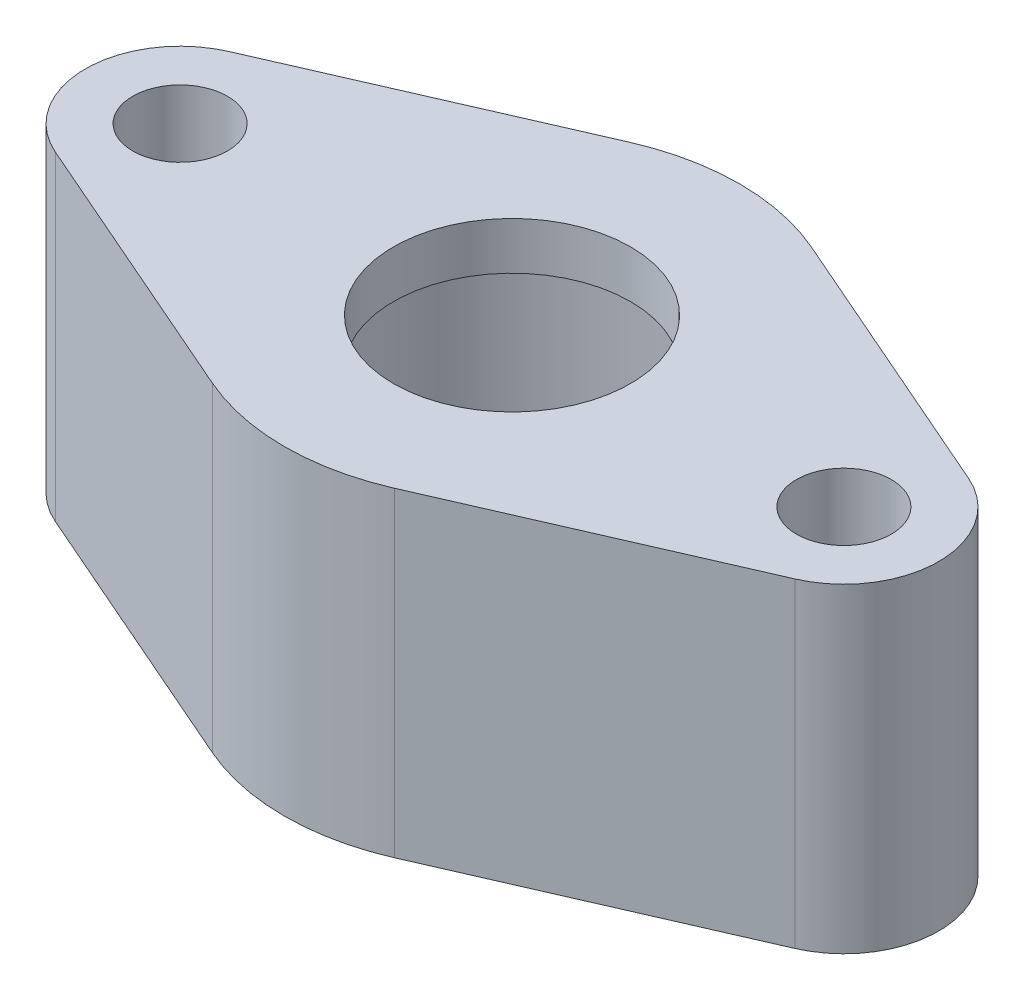
SolidWorks part; units mm, degrees
ref_plane "Front Plane" through (0, 0, 0) normal (0, 0, 1) x (1, 0, 0)
ref_plane "Top Plane" through (0, 0, 0) normal (0, 1, 0) x (1, 0, 0)
ref_plane "Right Plane" through (0, 0, 0) normal (1, 0, 0) x (0, 0, -1)
sketch "Sketch1" plane through (0, 0, 0) normal (0, 1, 0) x (1, 0, 0)
  line L0 (-3.84, 8.7985) -> (-15.6, 3.6661)
  line L1 (-15.6, -3.6661) -> (-3.84, -8.7985)
  line L2 (0, 0) -> (0, -7.6) construction
  line L3 (3.84, 8.7985) -> (15.6, 3.6661)
  line L4 (15.6, -3.6661) -> (3.84, -8.7985)
  circle A0 centre (0, 0) radius 7.6
  circle A1 centre (0, 0) radius 9.6
  arc A2 (-15.6, 3.6661) -> (-15.6, -3.6661) centre (-14, 0) ccw
  circle A3 centre (-14, 0) radius 2
  circle A4 centre (14, 0) radius 2
  arc A5 (15.6, 3.6661) -> (15.6, -3.6661) centre (14, 0) cw
  dimension "D1" = 15.2
  dimension "D3" = 4
  dimension "D4" = 4
  dimension "D5" = 14
  dimension "D2" = 2
extrude "Boss-Extrude1" add sketch "Sketch1" along normal blind 11.5 contours L0 A2 L1 A1 A3 | A1 A0 | A5 L3 A1 L4 A4
sketch "Sketch2" plane through (0, 11.5, 0) normal (0, 1, 0) x (1, 0, 0)
  line L4 (-3.84, 8.7985) -> (-15.6, 3.6661)
  line L5 (-15.6, -3.6661) -> (-3.84, -8.7985)
  line L6 (3.84, -8.7985) -> (15.6, -3.6661)
  line L7 (15.6, 3.6661) -> (3.84, 8.7985)
  line L8 (-3.84, 8.7985) -> (-15.6, 3.6661)
  line L9 (-15.6, -3.6661) -> (-3.84, -8.7985)
  line L10 (3.84, -8.7985) -> (15.6, -3.6661)
  line L11 (15.6, 3.6661) -> (3.84, 8.7985)
  circle A0 centre (0, 0) radius 5
  circle A1 centre (-14, 0) radius 2
  circle A2 centre (-14, 0) radius 2
  circle A3 centre (14, 0) radius 2
  circle A4 centre (14, 0) radius 2
  arc A8 (-15.6, 3.6661) -> (-15.6, -3.6661) centre (-14, 0) ccw
  arc A9 (-3.84, -8.7985) -> (3.84, -8.7985) centre (0, 0) ccw
  arc A10 (15.6, -3.6661) -> (15.6, 3.6661) centre (14, 0) ccw
  arc A11 (3.84, 8.7985) -> (-3.84, 8.7985) centre (0, 0) ccw
  arc A12 (-15.6, 3.6661) -> (-15.6, -3.6661) centre (-14, 0) ccw
  arc A13 (-3.84, -8.7985) -> (3.84, -8.7985) centre (0, 0) ccw
  arc A14 (15.6, -3.6661) -> (15.6, 3.6661) centre (14, 0) ccw
  arc A15 (3.84, 8.7985) -> (-3.84, 8.7985) centre (0, 0) ccw
  dimension "D4" = 10
  dimension "D1" = 0
  dimension "D2" = 0
  dimension "D3" = 0
extrude "Boss-Extrude2" add sketch "Sketch2" along normal blind 2
